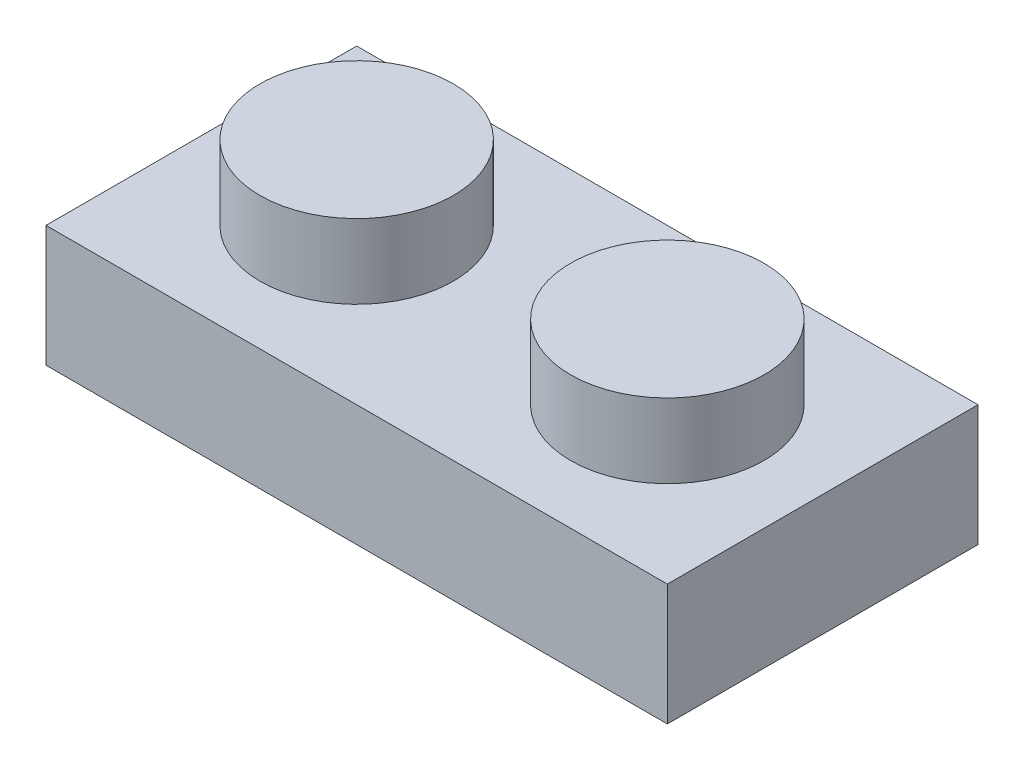
SolidWorks part; units mm, degrees
ref_plane "Front Plane" through (0, 0, 0) normal (0, 0, 1) x (1, 0, 0)
ref_plane "Top Plane" through (0, 0, 0) normal (0, 1, 0) x (1, 0, 0)
ref_plane "Right Plane" through (0, 0, 0) normal (1, 0, 0) x (0, 0, -1)
sketch "Sketch1" plane through (0, 0, 0) normal (0, 1, 0) x (1, 0, 0)
  line L0 (-49.2535, -6.1224) -> (-49.2535, -14.0724)
  line L1 (-49.2535, -14.0724) -> (-33.3535, -14.0724)
  line L2 (-33.3535, -14.0724) -> (-33.3535, -6.1224)
  line L3 (-33.3535, -6.1224) -> (-49.2535, -6.1224)
  dimension "D1" = 7.95
  dimension "D2" = 15.9
extrude "Boss-Extrude1" add sketch "Sketch1" along normal blind 3.1
sketch "Sketch2" plane through (0, 3.1, 0) normal (0, 1, 0) x (1, 0, 0)
  line L0 (-33.3535, -14.0724) -> (-33.3535, -6.1224) construction
  line L1 (-33.3535, -6.1224) -> (-49.2535, -6.1224) construction
  line L2 (-49.2535, -6.1224) -> (-49.2535, -14.0724) construction
  circle A0 centre (-45.2785, -10.0974) radius 2.475
  circle A1 centre (-37.3285, -10.0974) radius 2.475
  dimension "D1" = 4.95
  dimension "D2" = 4.95
  dimension "D3" = 3.975
  dimension "D4" = 3.975
  dimension "D5" = 3.975
  dimension "D6" = 3.975
extrude "Boss-Extrude2" add sketch "Sketch2" along normal blind 1.9
sketch "Sketch3" plane through (0, 0, 0) normal (0, -1, 0) x (1, 0, 0)
  line L0 (-47.7535, 12.5724) -> (-34.8535, 12.5724)
  line L1 (-34.8535, 12.5724) -> (-34.8535, 7.6224)
  line L2 (-34.8535, 7.6224) -> (-47.7535, 7.6224)
  line L3 (-47.7535, 7.6224) -> (-47.7535, 12.5724)
  line L4 (-49.2535, 6.1224) -> (-49.2535, 14.0724) construction
  line L5 (-49.2535, 14.0724) -> (-33.3535, 14.0724) construction
  line L6 (-33.3535, 14.0724) -> (-33.3535, 6.1224) construction
  line L7 (-33.3535, 6.1224) -> (-49.2535, 6.1224) construction
  dimension "D1" = 1.5
  dimension "D2" = 1.5
  dimension "D3" = 1.5
  dimension "D4" = 1.5
extrude "Cut-Extrude1" cut sketch "Sketch3" against normal blind 2
